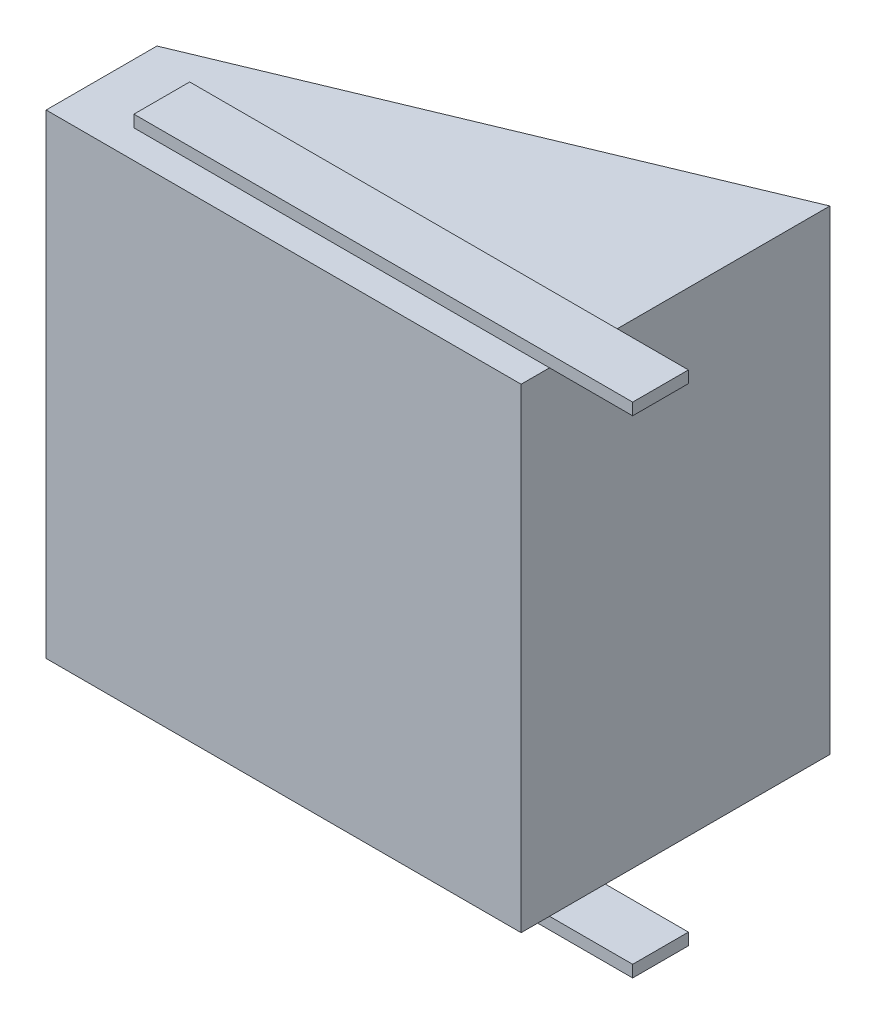
SolidWorks part; units mm, degrees
ref_plane "Front Plane" through (0, 0, 0) normal (0, 0, 1) x (1, 0, 0)
ref_plane "Top Plane" through (0, 0, 0) normal (0, 1, 0) x (1, 0, 0)
ref_plane "Right Plane" through (0, 0, 0) normal (1, 0, 0) x (0, 0, -1)
sketch "Sketch1" plane through (0, 0, 0) normal (0, 0, 1) x (1, 0, 0)
  line L1 (0, 0) -> (80, 0)
  line L2 (0, 0) -> (0, 80)
  line L3 (0, 80) -> (80, 80)
  line L4 (80, 0) -> (80, 80)
  dimension "D1" = 80
  dimension "D2" = 80
extrude "Boss-Extrude1" add sketch "Sketch1" along normal blind 2
sketch "Sketch2" plane through (0, 0, 0) normal (0, 0, -1) x (-1, 0, 0)
  line L0 (0, 80) -> (0, 0) construction
  line L1 (-80, 80) -> (0, 80)
  line L2 (-80, 80) -> (-80, 78)
  line L3 (-80, 78) -> (0, 78)
  line L4 (0, 80) -> (0, 78)
  line L6 (-80, 0) -> (0, 0)
  line L7 (-80, 0) -> (-80, 2)
  line L8 (-80, 2) -> (0, 2)
  line L9 (0, 0) -> (0, 2)
  dimension "D1" = 2
  dimension "D2" = 2
extrude "Boss-Extrude2" add sketch "Sketch2" along normal blind 50
sketch "Sketch3" plane through (0, 0, 0) normal (0, 0, -1) x (-1, 0, 0)
  line L0 (0, 2) -> (-80, 2) construction
  line L1 (-80, 78) -> (-78, 78)
  line L2 (-80, 78) -> (-80, 2)
  line L3 (-80, 2) -> (-78, 2)
  line L4 (-78, 78) -> (-78, 2)
  dimension "D1" = 2
extrude "Boss-Extrude3" add sketch "Sketch3" along normal blind 50
sketch "Sketch5" plane through (0, 80, 0) normal (0, 1, 0) x (1, 0, 0)
  line L0 (80, 50) -> (0, 16.6667)
  line L1 (0, -2) -> (0, 50) construction
  line L2 (0, 16.6667) -> (0, 50)
  line L3 (0, 50) -> (80, 50)
  dimension "D1" = 33.3333
extrude "Cut-Extrude2" cut sketch "Sketch5" against normal blind 100
sketch "Sketch6" plane through (0, 0, 0) normal (0, 0, -1) x (-1, 0, 0)
  line L0 (-78, 2) -> (0, 2) construction
  line L1 (0, 78) -> (-2, 78)
  line L2 (0, 78) -> (0, 2)
  line L3 (0, 2) -> (-2, 2)
  line L4 (-2, 78) -> (-2, 2)
  dimension "D1" = 2
extrude "Boss-Extrude4" add sketch "Sketch6" along normal blind 16.6667
sketch "Sketch7" plane through (0, 80, 0) normal (0, 1, 0) x (1, 0, 0)
  line L0 (0, -2) -> (0, 16.6667) construction
  line L1 (10, 12.1786) -> (94, 12.1786)
  line L2 (10, 12.1786) -> (10, 2.7866)
  line L3 (10, 2.7866) -> (94, 2.7866)
  line L4 (94, 12.1786) -> (94, 2.7866)
  dimension "D1" = 10
  dimension "D2" = 84
extrude "Boss-Extrude5" add sketch "Sketch7" against normal blind 82 and the other way blind 2
sketch "Sketch8" plane through (0, 0, -2.7866) normal (0, 0, 1) x (1, 0, 0)
  line L0 (94, 82) -> (94, -2) construction
  line L1 (80, 80) -> (94, 80)
  line L2 (80, 80) -> (80, 0)
  line L3 (80, 0) -> (94, 0)
  line L4 (94, 80) -> (94, 0)
  line L5 (10, -2) -> (94, -2) construction
  dimension "D1" = 2
extrude "Cut-Extrude3" cut sketch "Sketch8" against normal blind 50
equation "\"platform_length\"=80"
equation "\"D1@Sketch1\"=\"platform_length\""
equation "\"platform_width\"= 80"
equation "\"D2@Sketch1\"=\"platform_width\""
equation "\"metal_t\"=2"
equation "\"D1@Boss-Extrude1\"=\"metal_t\""
equation "\"D1@Sketch2\"= \"metal_t\""
equation "\"D2@Sketch2\"= \"metal_t\""
equation "\"D1@Boss-Extrude2\"=\"support_length\""
equation "\"D1@Sketch3\"= \"metal_t\""
equation "\"support_length\"=50"
equation "\"D1@Boss-Extrude3\"=\"support_length\""
equation "\"D1@Sketch5\"= \"support_length\"*2/3"
equation "\"D1@Sketch6\"=\"metal_t\""
equation "\"D1@Boss-Extrude4\"= \"support_length\"/3"
equation "\"D1@Sketch7\"= \"platform_length\"/8"
equation "\"D2@Sketch7\"=\"platform_length\"*7/8 + 14"
equation "\"D1@Boss-Extrude5\"=\"metal_t\" + \"platform_width\""
equation "\"D2@Boss-Extrude5\"= \"metal_t\""
equation "\"D1@Sketch8\"= \"metal_t\""
equation "\"D1@Cut-Extrude3\"= \"support_length\""
